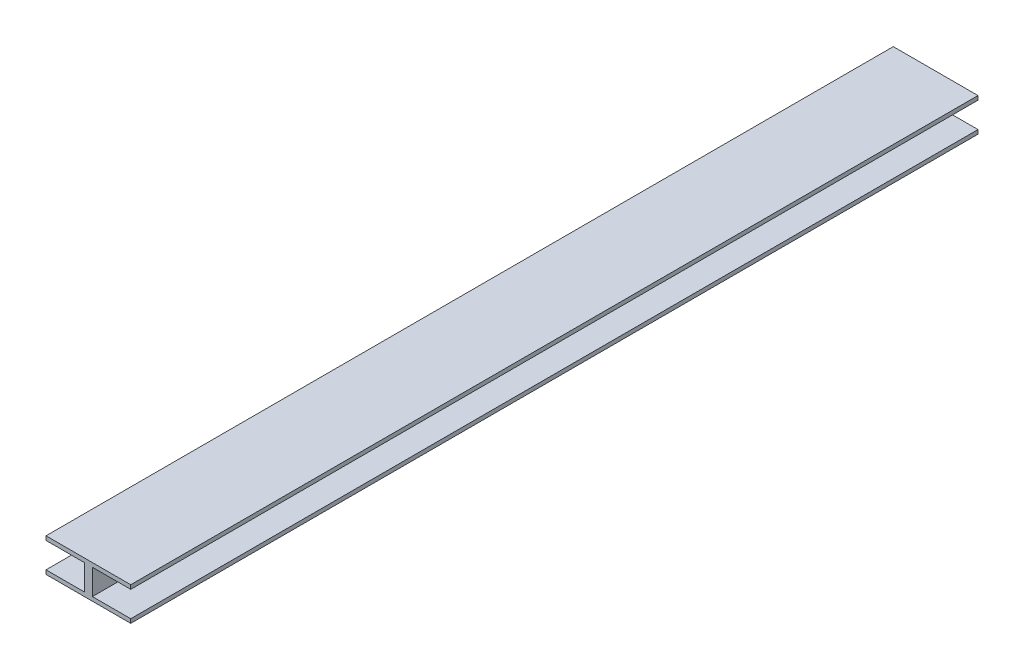
SolidWorks part; units mm, degrees
ref_plane "Alzado" through (0, 0, 0) normal (0, 0, 1) x (1, 0, 0)
ref_plane "Planta" through (0, 0, 0) normal (0, 1, 0) x (1, 0, 0)
ref_plane "Vista lateral" through (0, 0, 0) normal (1, 0, 0) x (0, 0, -1)
sketch "Croquis1" plane through (0, 0, 0) normal (0, 0, 1) x (1, 0, 0)
  line L0 (0, 19.7625) -> (-50, 19.7625)
  line L1 (0, 19.7625) -> (0, -19.7625)
  line L2 (0, -19.7625) -> (-50, -19.7625)
  line L3 (-4.7625, -15) -> (-50, -15)
  line L4 (-4.7625, 15) -> (-4.7625, -15)
  line L5 (-4.7625, 15) -> (-50, 15)
  line L6 (-50, -19.7625) -> (-50, -15)
  line L7 (-50, 19.7625) -> (-50, 15)
  line L8 (10.168, 0) -> (-43.4141, 0) construction
  line L9 (4.7625, 15) -> (4.7625, -15)
  line L10 (4.7625, 15) -> (50, 15)
  line L11 (50, 19.7625) -> (50, 15)
  line L12 (0, 19.7625) -> (50, 19.7625)
  line L13 (0, -19.7625) -> (50, -19.7625)
  line L14 (50, -19.7625) -> (50, -15)
  line L15 (4.7625, -15) -> (50, -15)
  line L16 (0, 19.7625) -> (0, -19.7625)
  line L17 (50, -19.7625) -> (50, -15)
  line L18 (4.7625, -15) -> (4.7625, 15)
  line L19 (50, 15) -> (50, 19.7625)
  dimension "D2" = 50
  dimension "D3" = 15
  dimension "D1" = 4.7625
extrude "Saliente-Extruir1" add sketch "Croquis1" along normal mid plane 1000 contours L8 L9 L10 L11 L12 L1 | L18 L8 L16 L13 L14 L15 | L8 L1 L0 L7 L5 L4 | L16 L8 L4 L3 L6 L2
